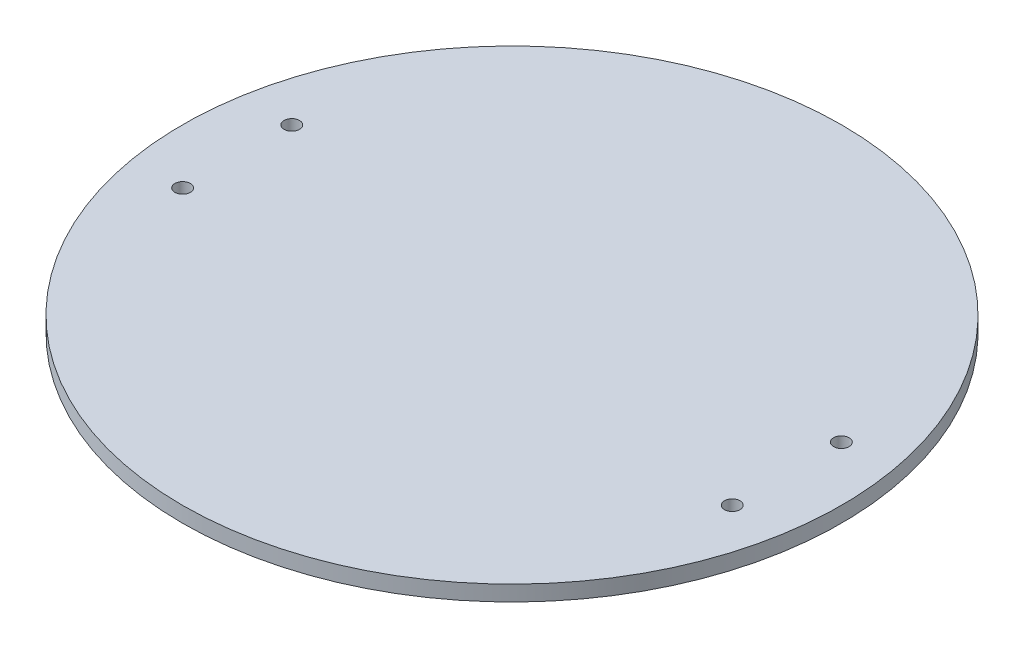
SolidWorks part; units mm, degrees
material "6061-T6 (SS)"
ref_plane "Front Plane" through (0, 0, 0) normal (0, 0, 1) x (1, 0, 0)
ref_plane "Top Plane" through (0, 0, 0) normal (0, 1, 0) x (1, 0, 0)
ref_plane "Right Plane" through (0, 0, 0) normal (1, 0, 0) x (0, 0, -1)
sketch "Sketch1" plane through (0, 0, 0) normal (0, 1, 0) x (1, 0, 0)
  circle A0 centre (0, 0) radius 85
  dimension "D1" = 170
extrude "Boss-Extrude1" add sketch "Sketch1" along normal mid plane 4
sketch "Sketch2" plane through (0, 2, 0) normal (0, 1, 0) x (1, 0, 0)
  line L0 (0, 85) -> (0, -85) construction
  line L1 (-85, 0) -> (85, 0) construction
  line L2 (70.87, 46.9302) -> (70.87, -46.9302) construction
  line L3 (-70.87, 46.9302) -> (-70.87, -46.9302) construction
  circle A0 centre (0, 0) radius 85 construction
  circle A1 centre (70.87, 14.075) radius 2
  circle A2 centre (70.87, -14.075) radius 2
  circle A3 centre (-70.87, -14.075) radius 2
  circle A4 centre (-70.87, 14.075) radius 2
  dimension "D1" = 4
  dimension "D2" = 28.15
  dimension "D3" = 141.74
extrude "Cut-Extrude1" cut sketch "Sketch2" against normal through all
